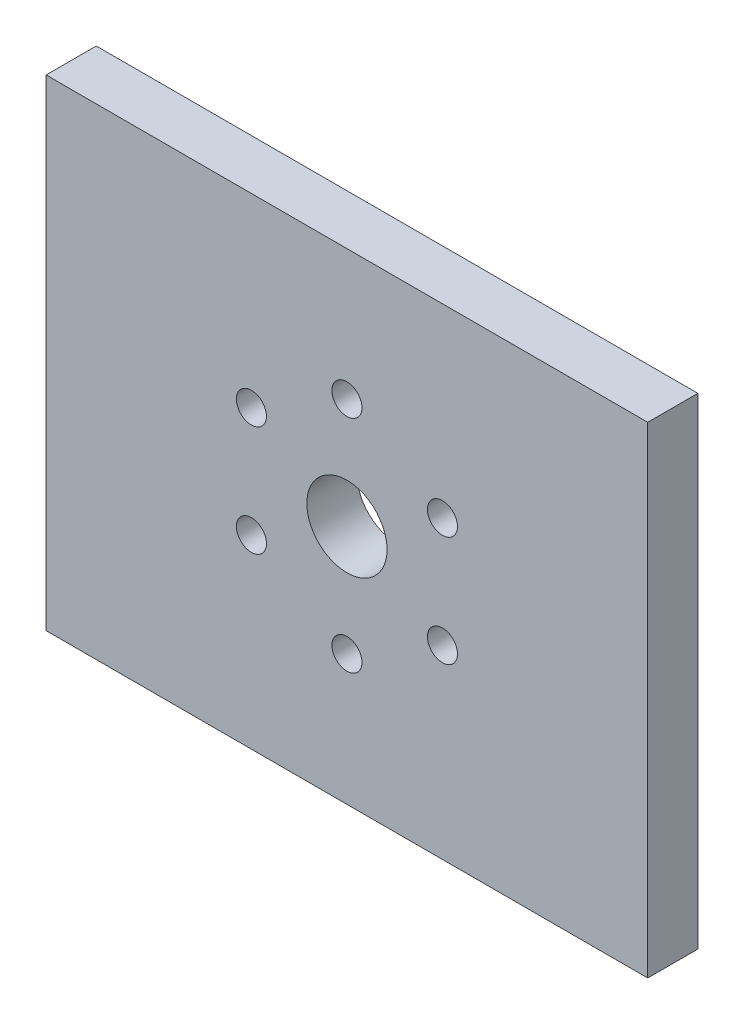
SolidWorks part; units mm, degrees
ref_plane "Front Plane" through (0, 0, 0) normal (0, 0, 1) x (1, 0, 0)
ref_plane "Top Plane" through (0, 0, 0) normal (0, 1, 0) x (1, 0, 0)
ref_plane "Right Plane" through (0, 0, 0) normal (1, 0, 0) x (0, 0, -1)
sketch "Sketch1" plane through (0, 0, 0) normal (0, 0, 1) x (1, 0, 0)
  line L0 (0, 0) -> (0, 73.2131) construction
  line L1 (0, 24) -> (0, 35) construction
  line L2 (0, 24) -> (9.5263, 29.5) construction
  line L3 (30, 0) -> (-30, 0)
  line L4 (-30, 0) -> (-30, 48)
  line L5 (-30, 48) -> (30, 48)
  line L6 (30, 0) -> (30, 48)
  circle A0 centre (0, 24) radius 19 construction
  circle A1 centre (0, 24) radius 11 construction
  circle A2 centre (0, 35) radius 1.5
  circle A3 centre (9.5263, 29.5) radius 1.5
  circle A4 centre (9.5263, 18.5) radius 1.5
  circle A5 centre (0, 13) radius 1.5
  circle A6 centre (-9.5263, 18.5) radius 1.5
  circle A7 centre (-9.5263, 29.5) radius 1.5
  circle A8 centre (0, 24) radius 4
  point P25 (0, 5)
  point P27 (0, 43)
  point P28 (0, 48)
  point P29 (0, 0)
  dimension "D1" = 38
  dimension "D2" = 22
  dimension "D3" = 3
  dimension "D7" = 5
  dimension "D10" = 8
  dimension "D5" = 60
  dimension "D6" = 11
  dimension "D8" = 60
  dimension "D9" = 5
  dimension "D4" = 6
extrude "Boss-Extrude1" add sketch "Sketch1" along normal blind 5
